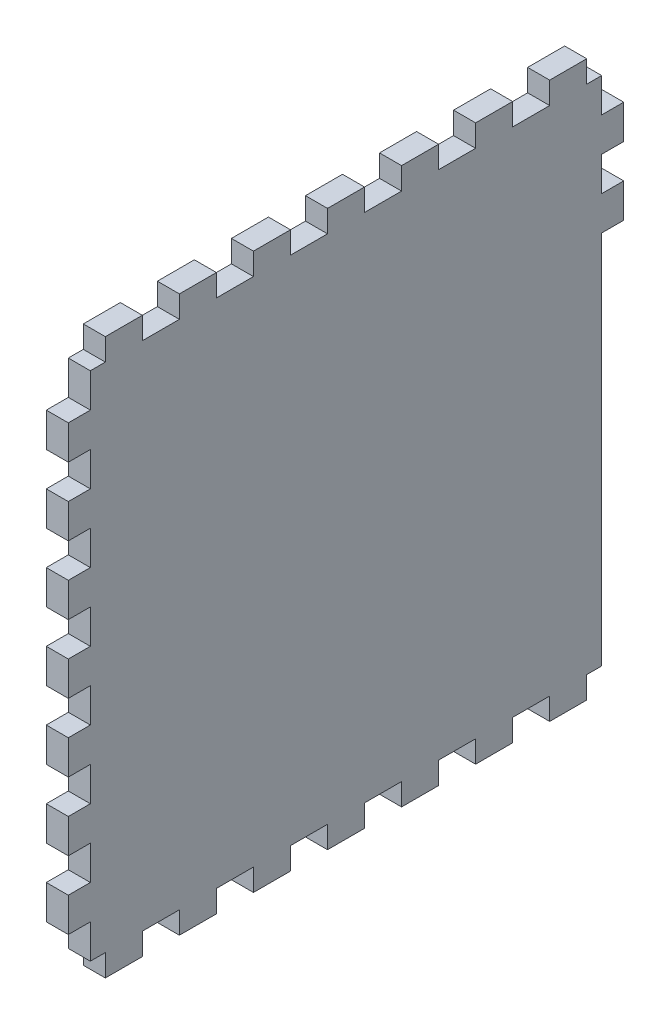
SolidWorks part; units mm, degrees
material "Acrylic (Medium-high impact)"
ref_plane "Front Plane" through (0, 0, 0) normal (0, 0, 1) x (1, 0, 0)
ref_plane "Top Plane" through (0, 0, 0) normal (0, 1, 0) x (1, 0, 0)
ref_plane "Right Plane" through (0, 0, 0) normal (1, 0, 0) x (0, 0, -1)
sketch "Sketch2" plane through (0, 0, 0) normal (1, 0, 0) x (0, 0, -1)
  line L1 (-40, -40) -> (40, -40)
  line L2 (-40, -40) -> (-40, 40)
  line L3 (-40, 40) -> (40, 40)
  line L4 (40, -40) -> (40, 40)
  line L5 (-40, -40) -> (40, 40) construction
  line L6 (-40, 40) -> (40, -40) construction
  point P0 (0, 0)
  dimension "D1" = 80
  dimension "D2" = 80
extrude "Boss-Extrude1" add sketch "Sketch2" along normal blind 3.175
sketch "Sketch3" plane through (3.175, 0, 0) normal (1, 0, 0) x (0, 0, -1)
  line L0 (0, 0) -> (50000, 0) construction
  line L1 (0, 0) -> (0, 50000) construction
  line L2 (34.6667, 36.825) -> (36.825, 36.825)
  line L3 (-29.3333, -40) -> (-29.3333, -36.825)
  line L4 (-29.3333, -36.825) -> (-24, -36.825)
  line L5 (-24, -40) -> (-18.6667, -40)
  line L6 (-34.6667, -40) -> (-29.3333, -40)
  line L8 (-34.6667, -36.825) -> (-34.6667, -40)
  line L9 (-24, -36.825) -> (-24, -40)
  line L10 (-18.6667, -40) -> (-18.6667, -36.825)
  line L11 (-18.6667, -36.825) -> (-13.3333, -36.825)
  line L12 (-13.3333, -40) -> (-8, -40)
  line L13 (-13.3333, -36.825) -> (-13.3333, -40)
  line L14 (-8, -40) -> (-8, -36.825)
  line L15 (-8, -36.825) -> (-2.6667, -36.825)
  line L16 (-2.6667, -40) -> (2.6667, -40)
  line L17 (-2.6667, -36.825) -> (-2.6667, -40)
  line L18 (2.6667, -40) -> (2.6667, -36.825)
  line L19 (2.6667, -36.825) -> (8, -36.825)
  line L20 (8, -40) -> (13.3333, -40)
  line L21 (8, -36.825) -> (8, -40)
  line L22 (13.3333, -40) -> (13.3333, -36.825)
  line L23 (13.3333, -36.825) -> (18.6667, -36.825)
  line L24 (18.6667, -40) -> (24, -40)
  line L25 (18.6667, -36.825) -> (18.6667, -40)
  line L26 (24, -40) -> (24, -36.825)
  line L27 (24, -36.825) -> (29.3333, -36.825)
  line L28 (29.3333, -40) -> (34.6667, -40)
  line L29 (29.3333, -36.825) -> (29.3333, -40)
  line L30 (34.6667, -40) -> (34.6667, -36.825)
  line L31 (34.6667, -36.825) -> (36.825, -36.825)
  line L32 (36.825, -36.825) -> (36.825, -31.915)
  line L33 (34.6667, 40) -> (34.6667, 36.825)
  line L34 (29.3333, 36.825) -> (29.3333, 40)
  line L35 (29.3333, 40) -> (34.6667, 40)
  line L36 (24, 36.825) -> (29.3333, 36.825)
  line L37 (24, 40) -> (24, 36.825)
  line L38 (18.6667, 36.825) -> (18.6667, 40)
  line L39 (18.6667, 40) -> (24, 40)
  line L40 (13.3333, 36.825) -> (18.6667, 36.825)
  line L41 (13.3333, 40) -> (13.3333, 36.825)
  line L42 (8, 36.825) -> (8, 40)
  line L43 (8, 40) -> (13.3333, 40)
  line L44 (2.6667, 36.825) -> (8, 36.825)
  line L45 (2.6667, 40) -> (2.6667, 36.825)
  line L46 (-2.6667, 36.825) -> (-2.6667, 40)
  line L47 (-2.6667, 40) -> (2.6667, 40)
  line L48 (-8, 36.825) -> (-2.6667, 36.825)
  line L49 (-8, 40) -> (-8, 36.825)
  line L50 (-13.3333, 36.825) -> (-13.3333, 40)
  line L51 (-13.3333, 40) -> (-8, 40)
  line L52 (-18.6667, 36.825) -> (-13.3333, 36.825)
  line L53 (-18.6667, 40) -> (-18.6667, 36.825)
  line L54 (-24, 36.825) -> (-24, 40)
  line L55 (-34.6667, 36.825) -> (-34.6667, 40)
  line L57 (-34.6667, 40) -> (-29.3333, 40)
  line L58 (-24, 40) -> (-18.6667, 40)
  line L59 (-29.3333, 36.825) -> (-24, 36.825)
  line L60 (-29.3333, 40) -> (-29.3333, 36.825)
  line L61 (36.825, -31.915) -> (40, -31.915)
  line L63 (40, -31.915) -> (40, -27.005)
  line L64 (40, 31.915) -> (36.825, 31.915)
  line L65 (36.825, -27.005) -> (40, -27.005)
  line L66 (36.825, -27.005) -> (36.825, -22.095)
  line L67 (36.825, -22.095) -> (40, -22.095)
  line L68 (40, -22.095) -> (40, -17.185)
  line L69 (36.825, -17.185) -> (40, -17.185)
  line L70 (36.825, -17.185) -> (36.825, -12.275)
  line L71 (36.825, -12.275) -> (40, -12.275)
  line L72 (40, -12.275) -> (40, -7.365)
  line L73 (36.825, -7.365) -> (40, -7.365)
  line L74 (36.825, -7.365) -> (36.825, -2.455)
  line L75 (36.825, -2.455) -> (40, -2.455)
  line L76 (40, -2.455) -> (40, 2.455)
  line L77 (36.825, 2.455) -> (40, 2.455)
  line L78 (36.825, 2.455) -> (36.825, 7.365)
  line L79 (36.825, 7.365) -> (40, 7.365)
  line L80 (40, 7.365) -> (40, 12.275)
  line L81 (36.825, 12.275) -> (40, 12.275)
  line L82 (36.825, 12.275) -> (36.825, 17.185)
  line L83 (36.825, 17.185) -> (40, 17.185)
  line L84 (40, 17.185) -> (40, 22.095)
  line L85 (36.825, 22.095) -> (40, 22.095)
  line L86 (36.825, 22.095) -> (36.825, 27.005)
  line L87 (36.825, 27.005) -> (40, 27.005)
  line L88 (40, 27.005) -> (40, 31.915)
  line L89 (36.825, 31.915) -> (36.825, 36.825)
  line L90 (0, 0) -> (-50000, 0) construction
  line L91 (-36.825, 31.915) -> (-36.825, 36.825)
  line L92 (-40, 27.005) -> (-40, 31.915)
  line L93 (-36.825, 27.005) -> (-40, 27.005)
  line L94 (-36.825, 22.095) -> (-36.825, 27.005)
  line L95 (-36.825, 22.095) -> (-40, 22.095)
  line L96 (-40, 17.185) -> (-40, 22.095)
  line L97 (-36.825, 17.185) -> (-40, 17.185)
  line L98 (-36.825, 12.275) -> (-36.825, 17.185)
  line L99 (-36.825, 12.275) -> (-40, 12.275)
  line L100 (-40, 7.365) -> (-40, 12.275)
  line L101 (-36.825, 7.365) -> (-40, 7.365)
  line L102 (-36.825, 2.455) -> (-36.825, 7.365)
  line L103 (-36.825, 2.455) -> (-40, 2.455)
  line L104 (-40, -2.455) -> (-40, 2.455)
  line L105 (-36.825, -2.455) -> (-40, -2.455)
  line L106 (-36.825, -7.365) -> (-36.825, -2.455)
  line L107 (-36.825, -7.365) -> (-40, -7.365)
  line L108 (-40, -12.275) -> (-40, -7.365)
  line L109 (-36.825, -12.275) -> (-40, -12.275)
  line L110 (-36.825, -17.185) -> (-36.825, -12.275)
  line L111 (-36.825, -17.185) -> (-40, -17.185)
  line L112 (-40, -22.095) -> (-40, -17.185)
  line L113 (-36.825, -22.095) -> (-40, -22.095)
  line L114 (-36.825, -27.005) -> (-36.825, -22.095)
  line L115 (-36.825, -27.005) -> (-40, -27.005)
  line L116 (-40, 31.915) -> (-36.825, 31.915)
  line L117 (-40, -31.915) -> (-40, -27.005)
  line L118 (-36.825, -31.915) -> (-40, -31.915)
  line L119 (-36.825, -36.825) -> (-36.825, -31.915)
  line L120 (-34.6667, -36.825) -> (-36.825, -36.825)
  line L121 (-34.6667, 36.825) -> (-36.825, 36.825)
  dimension "D1" = 7
extrude "Cut-Extrude1" cut sketch "Sketch3" against normal through all flip side to cut
sketch "Sketch4" plane through (3.175, 0, 0) normal (1, 0, 0) x (0, 0, -1)
  line L10 (36.825, 12.275) -> (40, 12.275)
  line L11 (36.825, 12.275) -> (36.825, -36.825)
  line L12 (36.825, -36.825) -> (40, -36.825)
  line L13 (40, 12.275) -> (40, -36.825)
extrude "Cut-Extrude2" cut sketch "Sketch4" against normal through all
